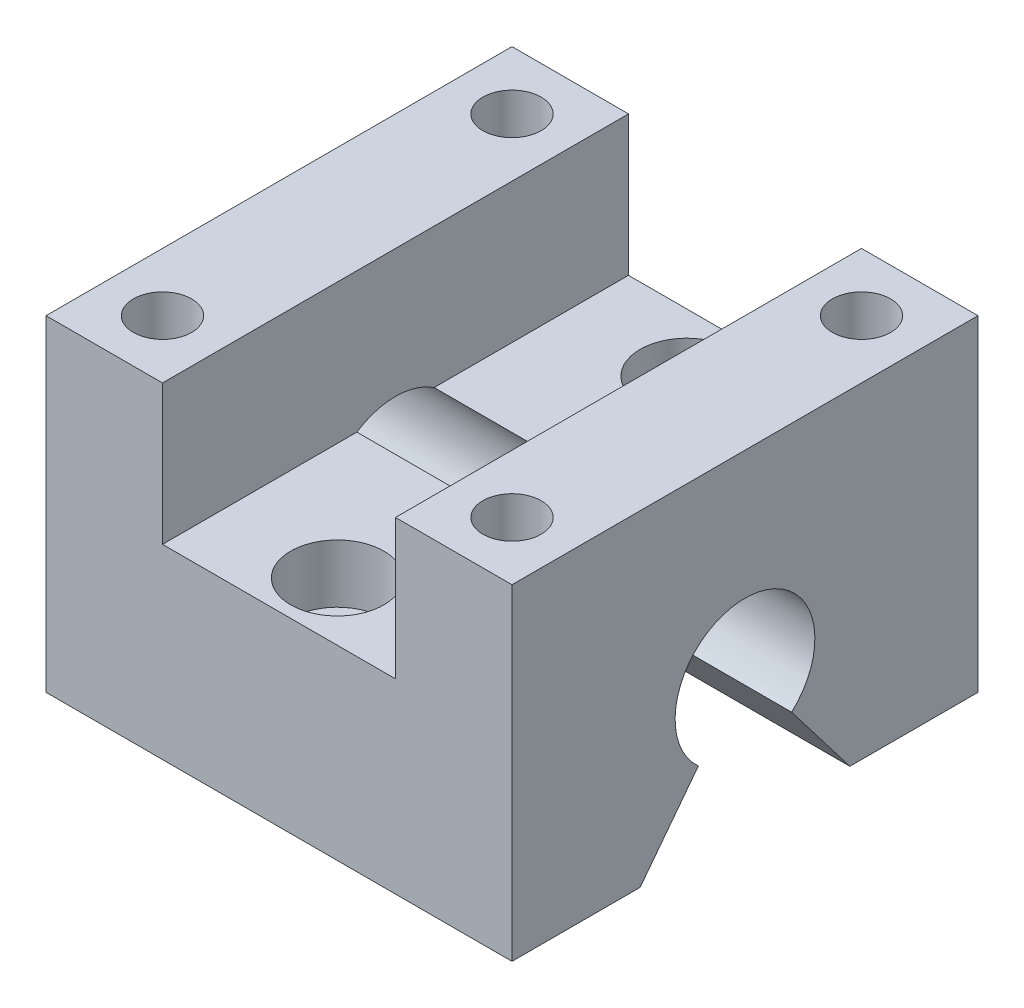
SolidWorks part; units mm, degrees
ref_plane "Спереди" through (0, 0, 0) normal (0, 0, 1) x (1, 0, 0)
ref_plane "Сверху" through (0, 0, 0) normal (0, 1, 0) x (1, 0, 0)
ref_plane "Справа" through (0, 0, 0) normal (1, 0, 0) x (0, 0, -1)
sketch "Эскиз1" plane through (0, 0, 0) normal (1, 0, 0) x (0, 0, -1)
  line L0 (-4, -7.4721) -> (-9, -14)
  line L1 (-20, -14) -> (-9, -14)
  line L2 (-20, -14) -> (-20, 14)
  line L3 (-20, 14) -> (20, 14)
  line L4 (20, -14) -> (20, 14)
  line L5 (0, 14) -> (0, -14) construction
  line L6 (-20, 0) -> (20, 0) construction
  line L11 (4, -7.4721) -> (9, -14)
  line L12 (9, -14) -> (20, -14)
  arc A1 (4, -7.4721) -> (-4, -7.4721) centre (0, -3) ccw
  point P0 (0, 0)
  dimension "D3" = 12
  dimension "D1" = 28
  dimension "D2" = 40
  dimension "D4" = 11
  dimension "D5" = 8
  dimension "D6" = 18
extrude "Бобышка-Вытянуть1" add sketch "Эскиз1" along normal mid plane 40
sketch "Эскиз2" plane through (0, 0, 0) normal (0, 0, 1) x (1, 0, 0)
  line L0 (0, 0) -> (0, 16.3424) construction
  line L1 (-10, 21.6164) -> (10, 21.6164)
  line L2 (-10, 21.6164) -> (-10, 2)
  line L3 (-10, 2) -> (10, 2)
  line L4 (10, 21.6164) -> (10, 2)
  line L5 (20, 14) -> (-20, 14) construction
  dimension "D1" = 20
  dimension "D2" = 12
extrude "Вырез-Вытянуть1" cut sketch "Эскиз2" against normal through all and the other way through all
sketch "Эскиз3" plane through (0, 2, 0) normal (0, 1, 0) x (1, 0, 0)
  line L0 (0, 0) -> (5.226, 0) construction
  circle A0 centre (0, 15) radius 4
  circle A1 centre (0, -15) radius 4
  dimension "D1" = 8
  dimension "D2" = 30
extrude "Вырез-Вытянуть2" cut sketch "Эскиз3" against normal blind 5
sketch "Эскиз4" plane through (0, 14, 0) normal (0, 1, 0) x (1, 0, 0)
  line L0 (0, 6.6125) -> (0, 0) construction
  line L1 (0, 0) -> (7.2525, 0) construction
  circle A0 centre (-15, 15) radius 2.5
  circle A1 centre (-15, -15) radius 2.5
  circle A2 centre (15, -15) radius 2.5
  circle A3 centre (15, 15) radius 2.5
  dimension "D1" = 5
  dimension "D2" = 30
  dimension "D3" = 30
extrude "Вырез-Вытянуть3" cut sketch "Эскиз4" against normal blind 10
